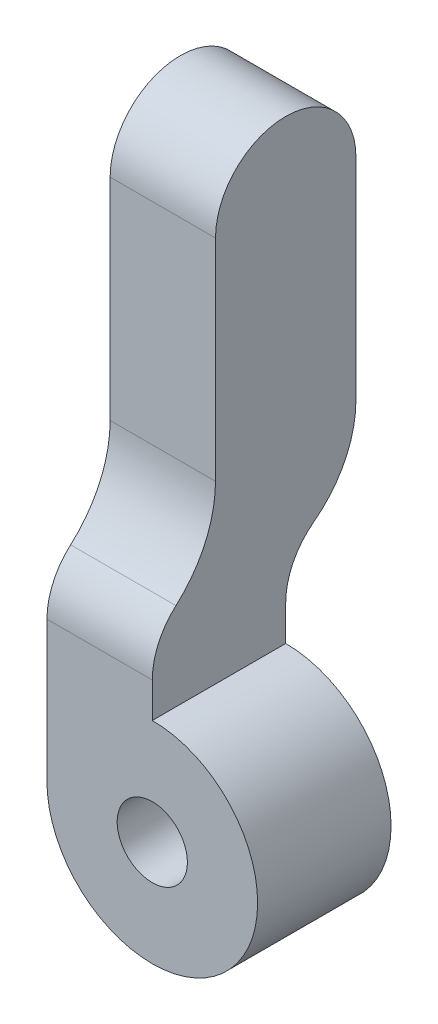
SolidWorks part; units mm, degrees
ref_plane "Alzado" through (0, 0, 0) normal (0, 0, 1) x (1, 0, 0)
ref_plane "Planta" through (0, 0, 0) normal (0, 1, 0) x (1, 0, 0)
ref_plane "Vista lateral" through (0, 0, 0) normal (1, 0, 0) x (0, 0, -1)
sketch "Croquis1" plane through (0, 0, 0) normal (0, 0, 1) x (1, 0, 0)
  circle A0 centre (0, 0) radius 1.5
  circle A1 centre (0, 0) radius 0.5
  dimension "D1" = 3
  dimension "D2" = 1
extrude "Saliente-Extruir1" add sketch "Croquis1" along normal blind 1.9
sketch "Croquis2" plane through (0, 0, 0) normal (1, 0, 0) x (0, 0, -1)
  line L0 (-1.9, 2) -> (-1.9, 1)
  line L1 (-1000, 0) -> (49000, 0) construction
  line L2 (-1, 4) -> (-1, 7)
  line L3 (1, 7) -> (1, 4)
  line L4 (0, 2) -> (0, 1)
  line L6 (-1.9, 1.5) -> (-1.9, -1.5) construction
  line L7 (-1.9, 1) -> (0, 1)
  line L8 (0, -1.5) -> (0, 1.5) construction
  arc A1 (-1.5632, 2.7484) -> (-1, 4) centre (-2.6722, 4) ccw
  arc A2 (-1, 7) -> (1, 7) centre (0, 7) cw
  arc A4 (0, 2) -> (0.4, 2.8) centre (1, 2) cw
  arc A5 (1, 4) -> (0.4, 2.8) centre (-0.5, 4) cw
  arc A6 (-1.9, 2) -> (-1.5632, 2.7484) centre (-0.9, 2) cw
  point P14 (1, 5.5)
  dimension "D2" = 1
  dimension "D3" = 7
  dimension "D4" = 1
  dimension "D5" = 1.5
  dimension "D1" = 2
  dimension "D6" = 1
  dimension "D7" = 2.9
extrude "Saliente-Extruir2" add sketch "Croquis2" against normal blind 1.5
sketch "Croquis3" plane through (0, 0, 1.9) normal (0, 0, 1) x (1, 0, 0)
  line L0 (-1.5, 1) -> (-1.5, 0)
  line L1 (-1.5, 1) -> (-1.118, 1) construction
  line L2 (-1.5, 1) -> (-1.118, 1)
  arc A0 (-1.118, 1) -> (0, 1.5) centre (0, 0) ccw construction
  arc A1 (-1.118, 1) -> (-1.5, 0) centre (0, 0) ccw
extrude "Saliente-Extruir3" add sketch "Croquis3" against normal up to surface (1.9 mm away) up to face at (-0.5893, 0.9761, 0)
sketch "Croquis4" [suppressed] plane through (0, 0, 0) normal (-1, 0, 0) x (0, 0, 1)
  line L0 (0, 2) -> (0, 1)
  line L1 (-998.1, 0) -> (49001.9, 0) construction
  line L2 (1, 4.0712) -> (1, 7)
  line L3 (3, 7) -> (3, 4.0712)
  line L4 (1.9, 2) -> (1.9, 1)
  line L5 (1.9, -1.5) -> (1.9, 1.5) construction
  line L7 (0, 1) -> (1.9, 1)
  line L9 (0, 1.5) -> (0, -1.5) construction
  arc A1 (0.3781, 2.7831) -> (1, 4.0712) centre (-0.645, 4.0712) ccw
  arc A2 (1, 7) -> (3, 7) centre (2, 7) cw
  arc A4 (1.9, 2) -> (2.34, 2.8285) centre (2.9, 2) cw
  arc A5 (3, 4.0712) -> (2.34, 2.8285) centre (1.5, 4.0712) cw
  arc A6 (0, 2) -> (0.3781, 2.7831) centre (1, 2) cw
  point P14 (3, 5.5356)
  dimension "D2" = 1
  dimension "D3" = 7
  dimension "D4" = 1
  dimension "D5" = 1.5
  dimension "D1" = 2
  dimension "D6" = 1
  dimension "D7" = 2.9
extrude "Saliente-Extruir4" [suppressed] add sketch "Croquis4" against normal blind 1.5
sketch "Croquis5" [suppressed] plane through (0, 0, 1.9) normal (0, 0, 1) x (1, 0, 0)
  line L0 (1.118, 1) -> (1.5, 1)
  line L1 (1.5, 1) -> (1.5, 0)
  arc A0 (0, 1.5) -> (1.118, 1) centre (0, 0) ccw construction
  arc A1 (1.5, 0) -> (1.118, 1) centre (0, 0) ccw
extrude "Saliente-Extruir5" [suppressed] add sketch "Croquis5" against normal up to surface (1.9 mm away)
